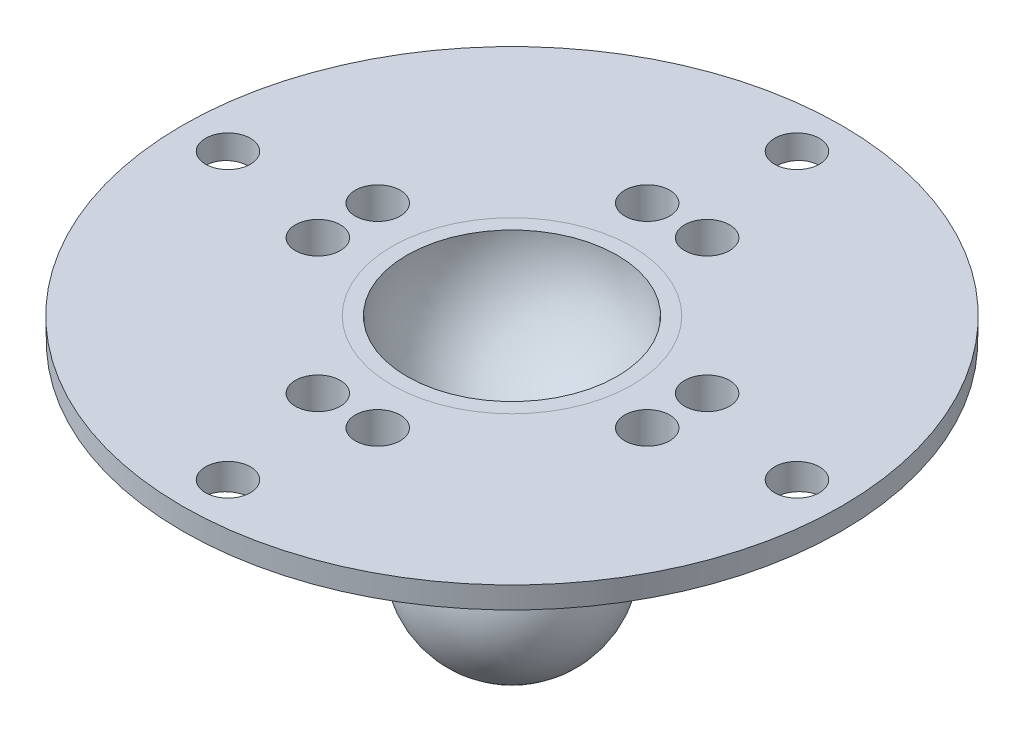
SolidWorks part; units mm, degrees
ref_plane "Front Plane" through (0, 0, 0) normal (0, 0, 1) x (1, 0, 0)
ref_plane "Top Plane" through (0, 0, 0) normal (0, 1, 0) x (1, 0, 0)
ref_plane "Right Plane" through (0, 0, 0) normal (1, 0, 0) x (0, 0, -1)
sketch "Sketch1" plane through (0, 0, 0) normal (1, 0, 0) x (0, 0, -1)
  line L0 (-0.0183, 24.8664) -> (-0.0077, 7.5) construction
  line L2 (-0.0077, 7.5) -> (-0.0056, 4) construction
  line L3 (-0.0056, 4) -> (0.0108, -22.8665) construction
  line L4 (3.9944, 4) -> (10.9944, 4)
  line L5 (3.795, 2.7527) -> (10.9821, 3.2671)
  line L6 (10.9944, 4) -> (10.9821, 3.2671)
  line L7 (0, 0.5) -> (0.0024, -0.5)
  line L8 (0.0026, -5.5) -> (0.0005, -6)
  line L9 (3.4944, 4) -> (3.9944, 4)
  line L10 (1.2613, 0.2059) -> (1.2629, -0.2781)
  line L11 (-0.0152, 10.3413) -> (-0.0154, -16.5251) construction
  arc A0 (0.0005, -6) -> (1.2629, -0.2781) centre (0.0014, -3) ccw
  arc A2 (3.8144, 2.8133) -> (-0.0031, 0) centre (-0.0056, 4) ccw
  arc A3 (0.0026, -5.5) -> (0.0024, -0.5) centre (0.0014, -3) ccw
  arc A4 (0, 0.5) -> (3.4944, 4) centre (-0.0056, 4) ccw
  arc A5 (-0.0031, 0) -> (1.2613, 0.2059) centre (-0.0056, 4) ccw construction
  arc A6 (1.2613, 0.2059) -> (3.795, 2.7527) centre (-0.0056, 4) ccw
  arc A7 (1.2629, -0.2781) -> (-0.0031, 0) centre (0.0014, -3) ccw construction
  arc A8 (-0.0031, 0) -> (0, 0) centre (0.0014, -3) ccw
  arc A9 (3.795, 2.7527) -> (3.9944, 4) centre (-0.0056, 4) ccw construction
  dimension "D1" = 6
  dimension "D2" = 4
  dimension "D4" = 2.5
  dimension "D5" = 3.5
  dimension "D3" = 7
revolve "Revolve5" add sketch "Sketch1" angle 360 about L11
ref_plane "Plane1" through (0, 4.0001, 0) normal (0, 1, 0) x (1, 0, 0)
sketch "Sketch2" plane through (0, 4.0001, 0) normal (0, 1, 0) x (1, 0, 0)
  line L0 (-11.0097, 0) -> (11.0097, 0) construction
  line L1 (0, 11.025) -> (0, -11.025) construction
  circle A0 centre (0, 0) radius 0.75
  circle A1 centre (0, -0.0153) radius 11.0097 construction
  circle A3 centre (-9.5, 0) radius 0.75
  circle A4 centre (1, -5.5) radius 0.75
  circle A5 centre (0, -9.5) radius 0.75
  circle A7 centre (0, 9.5) radius 0.75
  circle A9 centre (9.5, 0) radius 0.75
  circle A12 centre (-5.4995, 1) radius 0.75
  circle A13 centre (-5.4995, -1) radius 0.75
  circle A14 centre (-1, -5.5) radius 0.75
  circle A15 centre (5.4995, -1) radius 0.75
  circle A16 centre (5.4995, 1) radius 0.75
  circle A17 centre (1, 5.5) radius 0.75
  circle A18 centre (-1, 5.5) radius 0.75
  point P6 (0, 0)
  point P8 (0, 0)
  dimension "D1" = 1.5
  dimension "D2" = 1
  dimension "D5" = 1.5
  dimension "D9" = 1.5
  dimension "D13" = 1.5
  dimension "D3" = 9.5
  dimension "D6" = 5.5
  dimension "D7" = 9.5
  dimension "D11" = 1
  dimension "D12" = 5.4995
extrude "Cut-Extrude1" cut sketch "Sketch2" against normal blind 13
